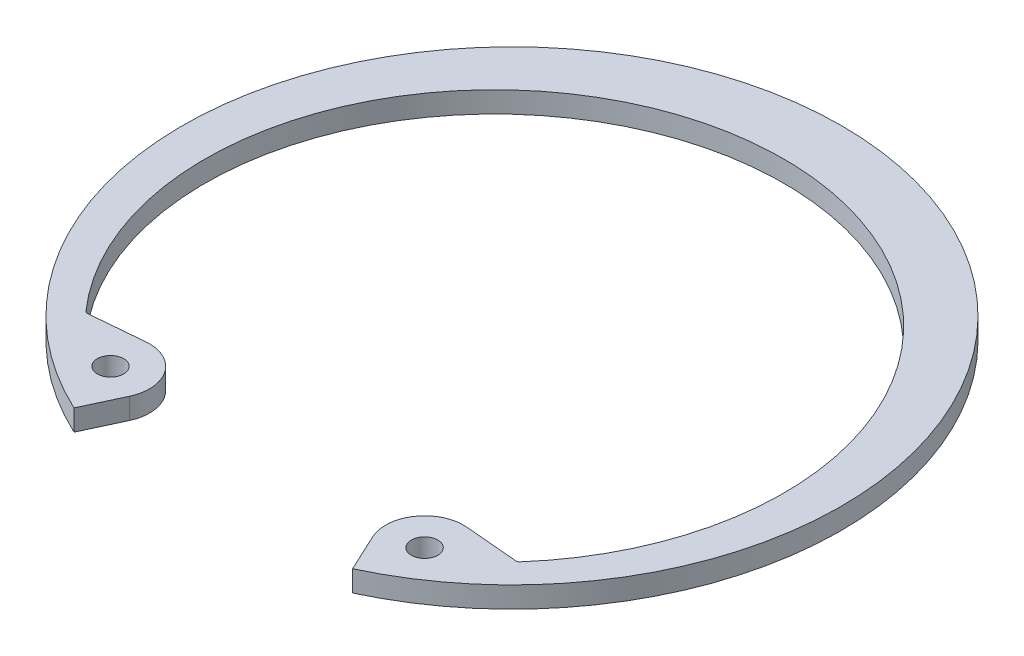
SolidWorks part; units mm, degrees
material "Cast Carbon Steel"
ref_plane "Front" through (0, 0, 0) normal (0, 0, 1) x (1, 0, 0)
ref_plane "Top" through (0, 0, 0) normal (0, 1, 0) x (1, 0, 0)
ref_plane "Right" through (0, 0, 0) normal (1, 0, 0) x (0, 0, -1)
sketch "Sketch2" plane through (0, 0, 0) normal (0, 1, 0) x (1, 0, 0)
  line L0 (0, 0) -> (0, -24.6634) construction
  line L1 (-16.1505, -15.7448) -> (-17.6601, -17.2164) construction
  line L2 (10.4232, -22.3526) -> (9.1054, -19.5267)
  line L3 (-10.4232, -22.3526) -> (-9.1054, -19.5267)
  line L4 (0, 20.3454) -> (0, 24.6634) construction
  line L5 (16.1505, -15.7448) -> (12.0073, -15.3823)
  line L6 (-16.1505, -15.7448) -> (-12.0073, -15.3823)
  line L7 (10.1738, -15.8347) -> (-0.9056, -22.9533) construction
  line L8 (-0.9056, -22.9533) -> (2.2523, -27.8682) construction
  line L9 (2.2523, -27.8682) -> (13.3317, -20.7497) construction
  line L10 (10.1738, -15.8347) -> (13.3317, -20.7497) construction
  line L11 (11.7528, -18.2922) -> (9.1054, -19.5267) construction
  line L12 (11.7528, -18.2922) -> (13.3317, -20.7497) construction
  line L13 (10.1738, -15.8347) -> (-10.1738, -15.8347) construction
  line L14 (-10.1738, -15.8347) -> (-13.3317, -20.7497) construction
  line L15 (-24.6634, 0) -> (24.6634, 0) construction
  arc A1 (10.4232, -22.3526) -> (-10.4232, -22.3526) centre (0, 0) ccw
  arc A2 (16.1505, -15.7448) -> (-16.1505, -15.7448) centre (0, -1.3134) ccw
  circle A3 centre (0, 0) radius 24.6634 construction
  arc A4 (9.1054, -19.5267) -> (12.0073, -15.3823) centre (11.7528, -18.2922) cw
  arc A5 (-9.1054, -19.5267) -> (-12.0073, -15.3823) centre (-11.7528, -18.2922) ccw
  circle A6 centre (11.7528, -18.2922) radius 0.9906
  circle A7 centre (-11.7528, -18.2922) radius 0.9906
  arc A8 (16.1505, -15.7448) -> (-16.1505, -15.7448) centre (0, -1.3134) cw construction
  circle A9 centre (0, 0) radius 16.637 construction
  point P5 (11.7528, -18.2922)
  point P10 (10.1738, -15.8347)
  dimension "D1" = 60
  dimension "D2" = 60
  dimension "L" = 33.274
  dimension "R" = 1.9812
  dimension "Df" = 49.3268
  dimension "H" = 5.842
  dimension "Angle" = 25
  dimension "Sec. Max" = 4.318
  dimension "Sec. Min" = 2.1082
extrude "Extrude1" add sketch "Sketch2" against normal blind 1.5748
fillet "Fillet1" radius 0.254 2 edges at (-16.1505, -0.7874, 15.7448) (16.1505, -0.7874, 15.7448)
sketch "Sketch3" plane through (0, 0, 0) normal (1, 0, 0) x (0, 0, -1)
  line L0 (-22.225, -16.4592) -> (-22.225, -1.651)
  line L1 (-22.225, -1.651) -> (-23.5966, -1.651)
  line L2 (-23.5966, -1.651) -> (-23.5966, 0.0762)
  line L3 (-23.5966, 0.0762) -> (-22.225, 0.0762)
  line L4 (-22.225, 0.0762) -> (-22.225, 2.4384)
  line L5 (-22.225, -16.4592) -> (-24.9682, -16.4592)
  line L6 (-22.225, -1.651) -> (0, -1.651) construction
  line L7 (-22.225, 2.4384) -> (-24.9682, 2.4384)
  line L8 (0, 130.3401) -> (0, 164.6301) construction
  line L9 (0, -1.651) -> (0, 0.0762) construction
  line L10 (0, 0.0762) -> (-22.225, 0.0762) construction
  line L11 (-23.5966, -0.7874) -> (0, -0.7874) construction
  line L12 (0, -135.0899) -> (0, 130.3401) construction
  line L13 (-15.6487, -1.5748) -> (20.3454, -1.5748) construction
  line L14 (-24.9682, -16.4592) -> (-24.9682, 2.4384)
  dimension "Shaft Lg" = 18.8976
  dimension "D1" = 0.7874
  dimension "D2" = 1.3716
  dimension "D4" = 1.3716
  dimension "D3" = 2.3622
revolve "Revolve1" [suppressed] add sketch "Sketch3" angle 360 about L8
delete or keep bodies "Body-Delete1" [suppressed] type delete bodies bodies 116
equation "\"D3@Sketch3\" = \"Shaft Lg@Sketch3\"/8"
equation "\"Shaft Lg@Sketch3\" = \"D1@Extrude1\"*12"
equation "\"D1@Sketch3\" = \"D1@Extrude1\"/2"
equation "\"D2@Sketch3\" = \"D4@Sketch3\""
